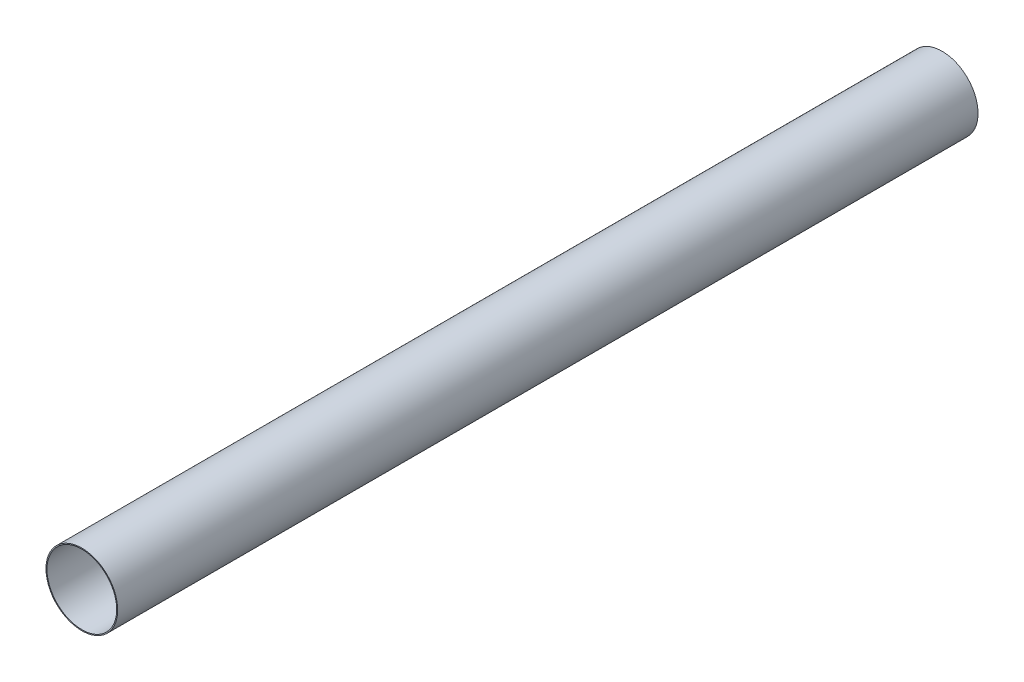
SolidWorks part; units mm, degrees
ref_plane "Plan de face" through (0, 0, 0) normal (0, 0, 1) x (1, 0, 0)
ref_plane "Plan de dessus" through (0, 0, 0) normal (0, 1, 0) x (1, 0, 0)
ref_plane "Plan de droite" through (0, 0, 0) normal (1, 0, 0) x (0, 0, -1)
sketch "Esquisse1" plane through (0, 0, 0) normal (0, 0, 1) x (1, 0, 0)
  circle A0 centre (0, 0) radius 50.8
  circle A1 centre (0, 0) radius 49.403
  dimension "D1" = 101.6
  dimension "D2" = 98.806
extrude "Boss.-Extru.1" add sketch "Esquisse1" along normal blind 1219.2
